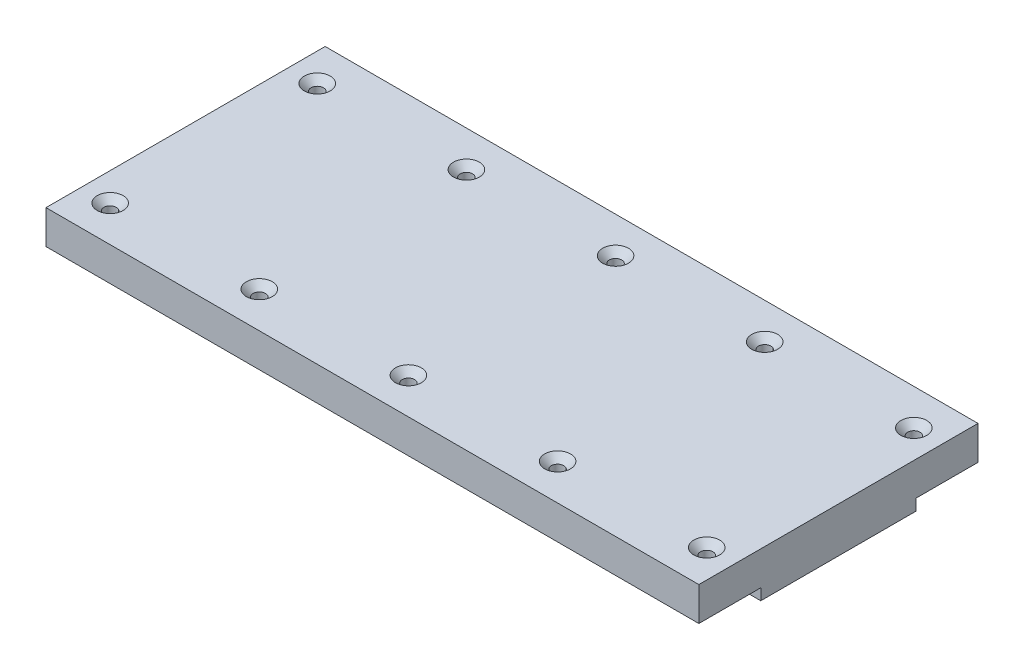
SolidWorks part; units mm, degrees
ref_plane "前基準面" through (0, 0, 0) normal (0, 0, 1) x (1, 0, 0)
ref_plane "上基準面" through (0, 0, 0) normal (0, 1, 0) x (1, 0, 0)
ref_plane "右基準面" through (0, 0, 0) normal (1, 0, 0) x (0, 0, -1)
sketch "草圖1" plane through (0, 0, 0) normal (0, 1, 0) x (1, 0, 0)
  line L1 (-290, -69) -> (290, -69)
  line L2 (-290, -69) -> (-290, 69)
  line L3 (-290, 69) -> (290, 69)
  line L4 (290, -69) -> (290, 69)
  line L5 (-290, -69) -> (290, 69) construction
  line L6 (-290, 69) -> (290, -69) construction
  point P0 (0, 0)
  dimension "D1" = 580
  dimension "D2" = 138
extrude "填料-伸長1" add sketch "草圖1" along normal blind 10
sketch "草圖2" plane through (0, 10, 0) normal (0, 1, 0) x (1, 0, 0)
  line L1 (-290, 124) -> (290, 124)
  line L2 (-290, 124) -> (-290, -124)
  line L3 (-290, -124) -> (290, -124)
  line L4 (290, 124) -> (290, -124)
  line L5 (-290, 124) -> (290, -124) construction
  line L6 (-290, -124) -> (290, 124) construction
  point P0 (0, 0)
  dimension "D1" = 580
  dimension "D2" = 248
extrude "填料-伸長2" add sketch "草圖2" along normal blind 30
sketch "草圖5" plane through (0, 40, 0) normal (0, 1, 0) x (1, 0, 0)
  line L0 (0, 92) -> (0, -92)
  line L1 (265, 92) -> (-265, 92)
  line L2 (265, 92) -> (265, -92)
  line L3 (265, -92) -> (-265, -92)
  line L4 (-265, 92) -> (-265, -92)
  line L5 (265, 92) -> (-265, -92) construction
  line L6 (265, -92) -> (-265, 92) construction
  line L7 (132.5, 92) -> (-132.5, 92)
  line L8 (132.5, 92) -> (132.5, -92)
  line L9 (132.5, -92) -> (-132.5, -92)
  line L10 (-132.5, 92) -> (-132.5, -92)
  line L11 (132.5, 92) -> (-132.5, -92) construction
  line L12 (132.5, -92) -> (-132.5, 92) construction
  point P0 (0, 0)
  point P6 (0, 0)
  dimension "D1" = 132.5
  dimension "D2" = 132.5
  dimension "D3" = 184
hole_wizard "M10 錐坑平頭螺釘的錐孔1" positions "3D草圖1" profile "草圖7" countersink size "M10" standard "ISO"
sketch3d "3D草圖1"
  point P0 (-265, 40, -92)
  point P3 (-265, 40, 92)
  point P6 (-132.5, 40, 92)
  point P9 (-132.5, 40, -92)
  point P12 (0, 40, -92)
  point P15 (0, 40, 92)
  point P18 (132.5, 40, 92)
  point P21 (265, 40, 92)
  point P24 (265, 40, -92)
  point P27 (132.5, 40, -92)
sketch "草圖7" plane through (-265, 40, -92) normal (1, 0, 0) x (0, 0, 1)
  line L0 (0, 0) -> (0, 62.3047)
  line L1 (0, 62.3047) -> (5.5, 59)
  line L2 (5.5, 59) -> (5.5, 6)
  line L3 (5.5, 6) -> (11.5, 0)
  line L5 (11.5, 0) -> (0, 0)
  line L6 (-5.5, 6) -> (-11.5, 0) construction
  line L10 (0, 62.3047) -> (-5.5, 59) construction
  line L11 (0, -6.35) -> (0, 107.95) construction
  dimension "鑽孔直徑" = 11
  dimension "鑽孔深度" = 59
  dimension "近端錐孔直徑" = 23
  dimension "近端錐孔角度" = 90
  dimension "導頭角度" = 118
